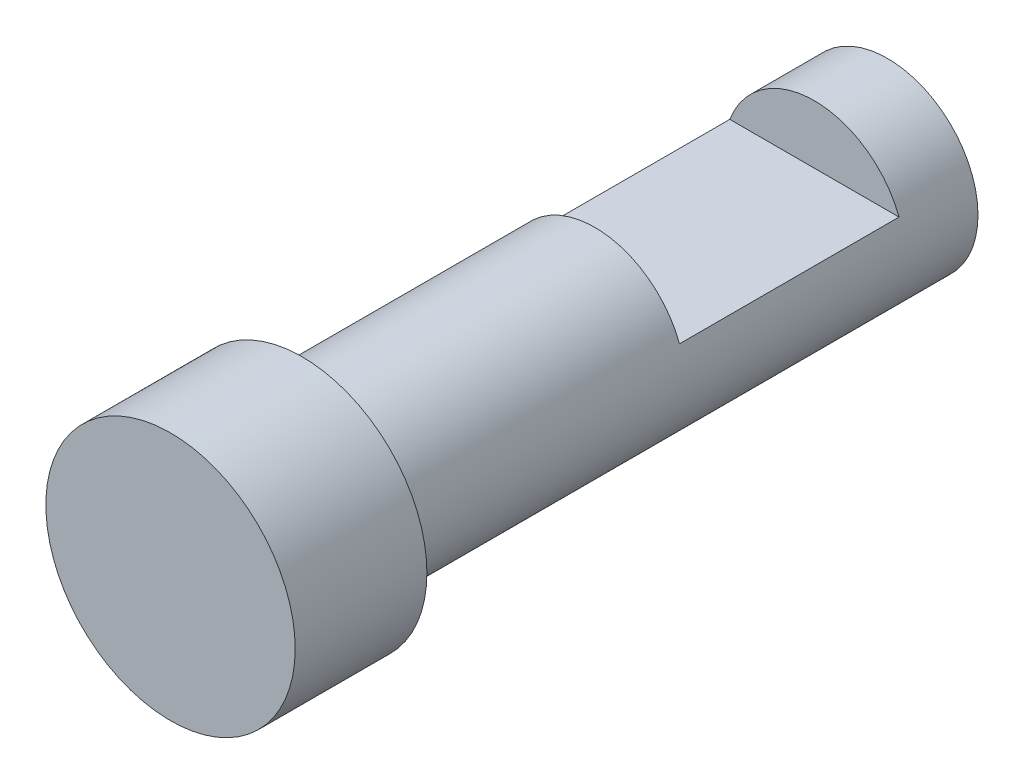
SolidWorks part; units mm, degrees
ref_plane "Front Plane" through (0, 0, 0) normal (0, 0, 1) x (1, 0, 0)
ref_plane "Top Plane" through (0, 0, 0) normal (0, 1, 0) x (1, 0, 0)
ref_plane "Right Plane" through (0, 0, 0) normal (1, 0, 0) x (0, 0, -1)
sketch "Sketch1" plane through (0, 0, 0) normal (0, 0, 1) x (1, 0, 0)
  circle A0 centre (0, 0) radius 5.4102
  dimension "D1" = 10.8204
extrude "Boss-Extrude1" add sketch "Sketch1" along normal blind 5.715
sketch "Sketch2" plane through (0, 0, 0) normal (0, 0, -1) x (-1, 0, 0)
  circle A0 centre (0, 0) radius 3.9243
  dimension "D1" = 7.8486
extrude "Boss-Extrude2" add sketch "Sketch2" along normal blind 25.4
ref_plane "Plane1" through (0, 3.9243, 0) normal (0, 1, 0) x (1, 0, 0)
sketch "Sketch3" plane through (0, 3.9243, 0) normal (0, 1, 0) x (1, 0, 0)
  line L0 (3.9243, 25.4) -> (-3.9243, 25.4) construction
  line L1 (-4.7822, 22.225) -> (4.2251, 22.225)
  line L2 (-4.7822, 22.225) -> (-4.7822, 12.7)
  line L3 (-4.7822, 12.7) -> (4.2251, 12.7)
  line L4 (4.2251, 22.225) -> (4.2251, 12.7)
  dimension "D1" = 3.175
  dimension "D2" = 9.525
extrude "Cut-Extrude1" cut sketch "Sketch3" against normal blind 2.54
